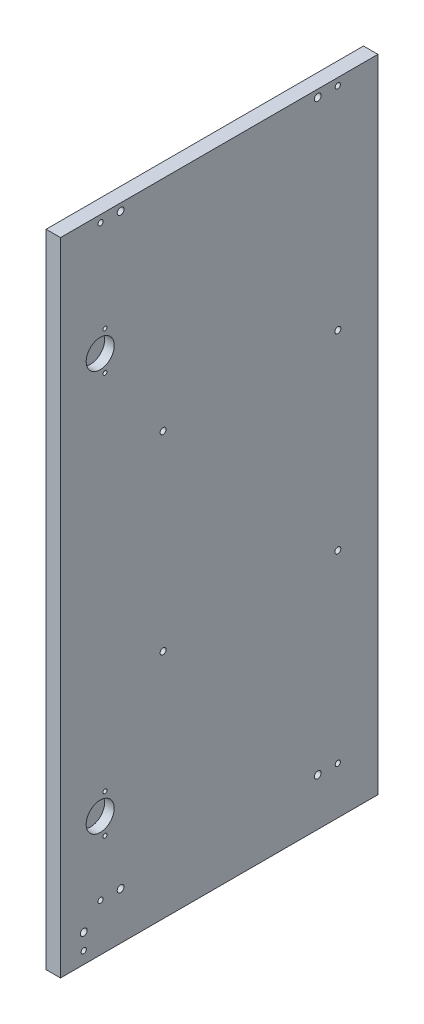
SolidWorks part; units mm, degrees
ref_plane "Front Plane" through (0, 0, 0) normal (0, 0, 1) x (1, 0, 0)
ref_plane "Top Plane" through (0, 0, 0) normal (0, 1, 0) x (1, 0, 0)
ref_plane "Right Plane" through (0, 0, 0) normal (1, 0, 0) x (0, 0, -1)
ref_plane "Back Plane" through (0, 0, -396) normal (0, 0, 1) x (1, 0, 0)
ref_plane "Bottom Plane" through (0, -800, 0) normal (0, 1, 0) x (-1, 0, 0)
ref_plane "Left Plane" through (-18, 0, 0) normal (1, 0, 0) x (0, 0, -1)
sketch "Sketch1" plane through (0, -800, 0) normal (0, 1, 0) x (-1, 0, 0)
  line L0 (55, -396) -> (-55, -396) construction
  line L1 (0, -396) -> (18, -396)
  line L2 (0, -396) -> (0, 0)
  line L3 (0, 0) -> (18, 0)
  line L4 (18, -396) -> (18, 0)
  line L5 (0, 55) -> (0, -55) construction
  line L6 (18, 55) -> (18, -55) construction
  line L7 (55, 0) -> (-55, 0) construction
extrude "Left Hand End" add sketch "Sketch1" along normal up to surface (800 mm away) up to plane "Top Plane"
sketch "Sketch3" plane through (0, 0, 0) normal (1, 0, 0) x (0, 0, -1)
  line L3 (0, 0) -> (0, -800) construction
  line L4 (396, 0) -> (396, -800) construction
  circle A0 centre (128, -511) radius 3.75
  circle A1 centre (346, -511) radius 3.75
  circle A2 centre (346, -273) radius 3.75
  circle A3 centre (128, -273) radius 3.75
  dimension "D5" = 7.5
  dimension "D1" = 273
  dimension "D2" = 238
  dimension "D3" = 128
  dimension "D4" = 50
extrude "Shelf Mount Holes" cut sketch "Sketch3" against normal blind 8
sketch "Sketch2" plane through (0, 0, 0) normal (1, 0, 0) x (0, 0, -1)
  line L0 (0, 0) -> (0, -800) construction
  line L1 (0, 0) -> (396, 0) construction
  line L2 (396, 0) -> (396, -800) construction
  line L3 (0, -800) -> (396, -800) construction
  circle A0 centre (50, -9) radius 3.25
  circle A1 centre (346, -9) radius 3.25
  circle A2 centre (75, -9) radius 4.25
  circle A3 centre (321, -9) radius 4.25
  circle A4 centre (50, -741) radius 3.25
  circle A5 centre (75, -741) radius 4.25
  circle A6 centre (321, -741) radius 4.25
  circle A7 centre (346, -741) radius 3.25
  circle A8 centre (29, -765) radius 4.25
  circle A9 centre (29, -785) radius 3.25
  dimension "D3" = 6.5
  dimension "D7" = 8.5
  dimension "D1" = 50
  dimension "D2" = 9
  dimension "D4" = 50
  dimension "D5" = 75
  dimension "D6" = 75
  dimension "D8" = 59
  dimension "D9" = 29
  dimension "D10" = 15
  dimension "D11" = 35
extrude "Base and Top Mount Holes" cut sketch "Sketch2" against normal blind 12
sketch "Sketch4" plane through (0, 0, 0) normal (1, 0, 0) x (0, 0, -1)
  line L1 (0, -800) -> (396, -800) construction
  line L2 (0, 0) -> (396, 0) construction
  line L3 (49.5, -116.3023) -> (49.5, -178.8152) construction
  line L4 (55.5, -116.3023) -> (55.5, -178.8152) construction
  line L5 (0, 0) -> (0, -800) construction
  line L6 (55.5, -465.5887) -> (55.5, -834.4113) construction
  line L7 (49.5, -465.5887) -> (49.5, -834.4113) construction
  circle A0 centre (49.5, -650) radius 17.5
  circle A1 centre (55.5, -626) radius 2.5
  circle A2 centre (55.5, -674) radius 2.5
  circle A3 centre (49.5, -150) radius 17.5
  circle A4 centre (55.5, -126) radius 2.5
  circle A5 centre (55.5, -174) radius 2.5
  dimension "D1" = 35
  dimension "D2" = 150
  dimension "D3" = 5
  dimension "D7" = 35
  dimension "D8" = 5
  dimension "D4" = 6
  dimension "D5" = 24
  dimension "D6" = 49.5
  dimension "D9" = 24
  dimension "D10" = 150
  dimension "D11" = 24
  dimension "D13" = 24
  dimension "D12" = 6
extrude "Hinge Holes" cut sketch "Sketch4" against normal blind 12
move or copy body "Corpo-Sposta/copia1" [suppressed] bodies to move or copy 111
